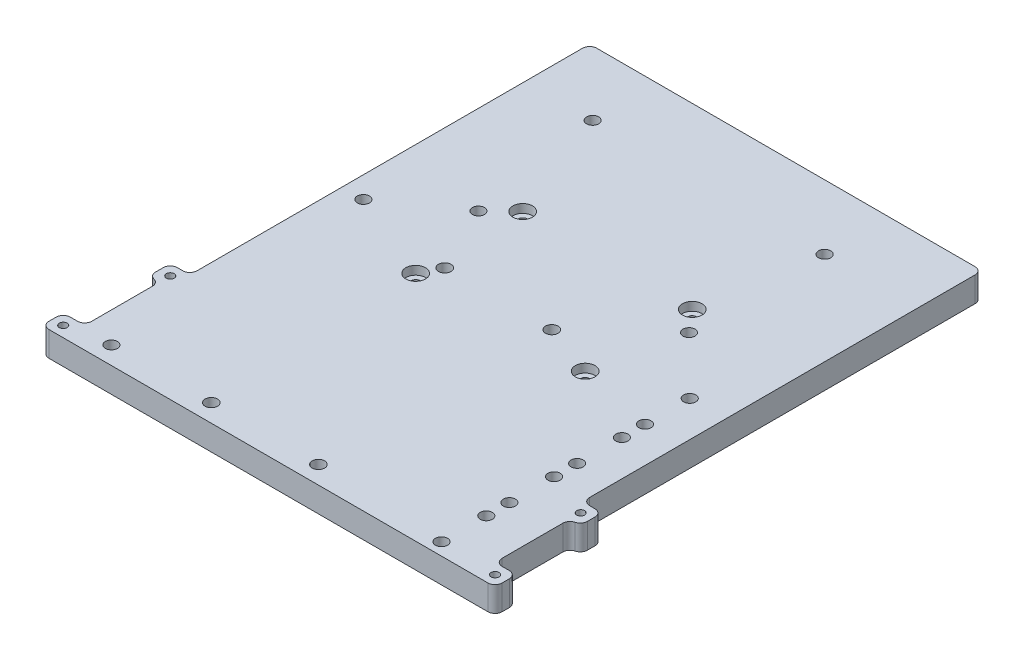
SolidWorks part; units mm, degrees
material "PLA2"
ref_plane "Front Plane" through (0, 0, 0) normal (0, 0, 1) x (1, 0, 0)
ref_plane "Top Plane" through (0, 0, 0) normal (0, 1, 0) x (1, 0, 0)
ref_plane "Right Plane" through (0, 0, 0) normal (1, 0, 0) x (0, 0, -1)
sketch "Sketch1" plane through (0, 0, 0) normal (0, 1, 0) x (1, 0, 0)
  line L0 (0, 0) -> (0, 21914.9783) construction
  line L1 (0, 0) -> (21914.9783, 0) construction
  circle A0 centre (-30.1625, 19.05) radius 1.5875
  circle A1 centre (-30.1625, 19.05) radius 4.445
  circle A2 centre (-30.1625, -19.05) radius 4.445
  circle A3 centre (-30.1625, -19.05) radius 1.5875
  circle A4 centre (30.1625, -19.05) radius 1.5875
  circle A5 centre (30.1625, -19.05) radius 4.445
  circle A6 centre (30.1625, 19.05) radius 4.445
  circle A7 centre (30.1625, 19.05) radius 1.5875
  dimension "D1" = 3.175
  dimension "D2" = 8.89
  dimension "D3" = 60.325
  dimension "D4" = 38.1
sketch "Sketch2" plane through (0, 0, 0) normal (0, 1, 0) x (1, 0, 0)
  line L0 (0, 0) -> (0, -50000) construction
  line L1 (0, 0) -> (50000, 0) construction
  line L2 (-69.85, 0) -> (-69.85, 82.55)
  line L3 (-69.85, 82.55) -> (69.85, 82.55)
  line L4 (69.85, 0) -> (69.85, 82.55)
  line L5 (-69.85, 0) -> (-69.85, -101.6)
  line L6 (-69.85, -101.6) -> (69.85, -101.6)
  line L7 (69.85, 0) -> (69.85, -101.6)
  circle A0 centre (30.1625, 19.05) radius 1.5875 construction
  circle A1 centre (30.1625, -19.05) radius 1.5875 construction
  circle A2 centre (-30.1625, -19.05) radius 1.5875 construction
  circle A3 centre (-30.1625, 19.05) radius 1.5875 construction
  circle A4 centre (30.1625, 19.05) radius 1.5875
  circle A5 centre (30.1625, -19.05) radius 1.5875
  circle A6 centre (-30.1625, -19.05) radius 1.5875
  circle A7 centre (-30.1625, 19.05) radius 1.5875
  point P9 (0, 82.55)
  point P13 (0, -101.6)
  dimension "D1" = 139.7
  dimension "D2" = 82.55
  dimension "D3" = 101.6
extrude "MainPlate" add sketch "Sketch2" along normal blind 8.89
sketch "Sketch3" plane through (0, 8.89, 0) normal (0, 1, 0) x (1, 0, 0)
  circle A0 centre (-30.1625, 19.05) radius 3.4925
  circle A1 centre (30.1625, 19.05) radius 3.4925
  circle A2 centre (-30.1625, -19.05) radius 3.4925
  circle A3 centre (30.1625, -19.05) radius 3.4925
  dimension "D1" = 6.985
  dimension "D2" = 6.985
  dimension "D3" = 6.985
  dimension "D4" = 6.985
extrude "CasterWheel_MountHoles" cut sketch "Sketch3" against normal blind 3.048
sketch "Sketch4" plane through (0, 8.89, 0) normal (0, 1, 0) x (1, 0, 0)
  line L1 (-45.8122, 59.5876) -> (36.7378, 59.5876) construction
  line L2 (-45.8122, 59.5876) -> (-38.1922, 11.3276) construction
  line L3 (-38.1922, 11.3276) -> (36.7378, 11.3276) construction
  line L4 (36.7378, 59.5876) -> (36.7378, 11.3276) construction
  line L5 (-45.8122, 59.5876) -> (36.7378, 11.3276) construction
  line L6 (-38.1922, 11.3276) -> (36.7378, 59.5876) construction
  circle A0 centre (-45.8122, 59.5876) radius 2.159
  circle A1 centre (-38.1922, 11.3276) radius 2.159
  circle A2 centre (36.7378, 59.5876) radius 2.159
  circle A3 centre (36.7378, 11.3276) radius 2.159
  point P0 (-2.54, 34.29)
  dimension "D1" = 4.318
  dimension "D2" = 34.29
  dimension "D3" = 2.54
  dimension "D4" = 48.26
  dimension "D5" = 82.55
  dimension "D6" = 74.93
extrude "Arduino_MountHoles" cut sketch "Sketch4" against normal blind 6.35
sketch "Sketch5" plane through (0, 8.89, 0) normal (0, 1, 0) x (1, 0, 0)
  line L0 (-62.23, -5.588) -> (-62.23, -95.25) construction
  line L1 (-69.85, -101.6) -> (69.85, -101.6) construction
  line L2 (-69.85, 82.55) -> (-69.85, -101.6) construction
  circle A0 centre (-62.23, -5.588) radius 2.159
  circle A1 centre (-62.23, -95.25) radius 2.159
  dimension "D3" = 4.318
  dimension "D1" = 89.662
  dimension "D2" = 6.35
  dimension "D4" = 7.62
extrude "PDB_16A_MountingHoles" cut sketch "Sketch5" against normal blind 6.35
sketch "Sketch6" plane through (0, 8.89, 0) normal (0, 1, 0) x (1, 0, 0)
  line L0 (-26.67, -12.192) -> (-26.67, -95.25) construction
  line L1 (-69.85, -101.6) -> (69.85, -101.6) construction
  line L2 (-26.67, -53.721) -> (11.43, -53.721) construction
  line L3 (-7.62, -53.721) -> (-7.62, -101.6) construction
  circle A0 centre (-26.67, -95.25) radius 2.2322
  circle A1 centre (-26.67, -12.192) radius 2.2322
  circle A2 centre (11.43, -12.192) radius 2.2322
  circle A3 centre (11.43, -95.25) radius 2.2322
  circle A4 centre (-62.23, -95.25) radius 2.159 construction
  dimension "D1" = 83.058
  dimension "D2" = 6.35
  dimension "D3" = 38.1
  dimension "D4" = 35.56
extrude "PDB_15A_MountingHoles" cut sketch "Sketch6" against normal blind 6.35
sketch "Sketch7" plane through (0, 8.89, 0) normal (0, 1, 0) x (1, 0, 0)
  line L0 (57.15, -81.2165) -> (57.15, -97.155) construction
  line L1 (-69.85, -101.6) -> (69.85, -101.6) construction
  line L2 (-69.85, 82.55) -> (-69.85, -101.6) construction
  circle A0 centre (57.15, -97.155) radius 2.159
  circle A1 centre (57.15, -81.2165) radius 2.159
  dimension "D1" = 4.318
  dimension "D2" = 15.9385
  dimension "D3" = 4.445
  dimension "D4" = 127
extrude "DRV8871_MountingHoles" cut sketch "Sketch7" against normal blind 6.35
pattern_linear "DRV8871_MountPattern" count 4 spacing 24.13 along (0, 0, -1) of "DRV8871_MountingHoles"
sketch "Sketch8" plane through (0, 0, 0) normal (0, -1, 0) x (1, 0, 0)
  line L0 (0, 0) -> (0, 63.5) construction
  line L1 (-69.85, 101.6) -> (69.85, 101.6) construction
  line L2 (-69.85, 101.6) -> (-69.85, 66.675)
  line L3 (-69.85, 66.675) -> (69.85, 66.675)
  line L5 (69.215, 63.5) -> (-69.215, 63.5)
  line L6 (-69.215, 63.5) -> (-69.215, 59.69)
  line L7 (-69.215, 59.69) -> (-76.835, 59.69)
  line L8 (-76.835, 59.69) -> (-76.835, 67.31)
  line L9 (-76.835, 67.31) -> (-73.025, 67.31)
  line L10 (-73.025, 67.31) -> (-73.025, 93.98)
  line L11 (-73.025, 93.98) -> (-80.645, 93.98)
  line L12 (-80.645, 93.98) -> (-80.645, 101.6)
  line L13 (-80.645, 101.6) -> (-69.85, 101.6)
  line L14 (80.645, 101.6) -> (69.85, 101.6)
  line L15 (80.645, 93.98) -> (80.645, 101.6)
  line L16 (73.025, 93.98) -> (80.645, 93.98)
  line L17 (73.025, 67.31) -> (73.025, 93.98)
  line L18 (76.835, 67.31) -> (73.025, 67.31)
  line L19 (76.835, 59.69) -> (76.835, 67.31)
  line L20 (69.215, 59.69) -> (76.835, 59.69)
  line L21 (69.215, 63.5) -> (69.215, 59.69)
  line L22 (69.85, 101.6) -> (69.85, 66.675)
  line L23 (-76.835, 93.98) -> (-76.835, 101.6) construction
  line L24 (0, 66.675) -> (0, 101.6) construction
  line L25 (-73.025, 59.69) -> (-73.025, 67.31) construction
  line L26 (-69.85, -82.55) -> (-69.85, 101.6) construction
  circle A0 centre (-76.835, 97.79) radius 1.397
  circle A1 centre (-73.025, 63.5) radius 1.397
  circle A2 centre (73.025, 63.5) radius 1.397
  circle A3 centre (76.835, 97.79) radius 1.397
  dimension "D11" = 2.794
  dimension "D12" = 2.794
  dimension "D1" = 3.175
  dimension "D2" = 3.175
  dimension "D3" = 3.81
  dimension "D4" = 3.81
  dimension "D5" = 7.62
  dimension "D6" = 7.62
  dimension "0.3" = 7.62
  dimension "D10" = 7.62
  dimension "D8" = 34.29
  dimension "D9" = 146.05
  dimension "D7" = 153.67
extrude "Boss-Extrude1" add sketch "Sketch8" against normal up to surface (8.89 mm away) up to face at (57.15, 8.89, 59.2455)
fillet "Fillet1" radius 2.54 6 edges at (-73.025, 4.445, 67.31) (-69.85, 4.445, 59.69) (-73.025, 4.445, 93.98) (73.025, 4.445, 93.98) (73.025, 4.445, 67.31) (69.85, 4.445, 59.69)
fillet "Fillet2" radius 2.54 10 edges at (-69.85, 4.445, -82.55) (-76.835, 4.445, 59.69) (-76.835, 4.445, 67.31) (-80.645, 4.445, 93.98) (-80.645, 4.445, 101.6) (69.85, 4.445, -82.55) (76.835, 4.445, 59.69) (76.835, 4.445, 67.31) (80.645, 4.445, 93.98) (80.645, 4.445, 101.6)
equation "\"D2@Sketch3\"=\"D1@Sketch3\""
equation "\"D3@Sketch3\"=\"D1@Sketch3\""
equation "\"D4@Sketch3\"=\"D1@Sketch3\""
equation "\"D2@Sketch8\"=\"D1@Sketch8\""
